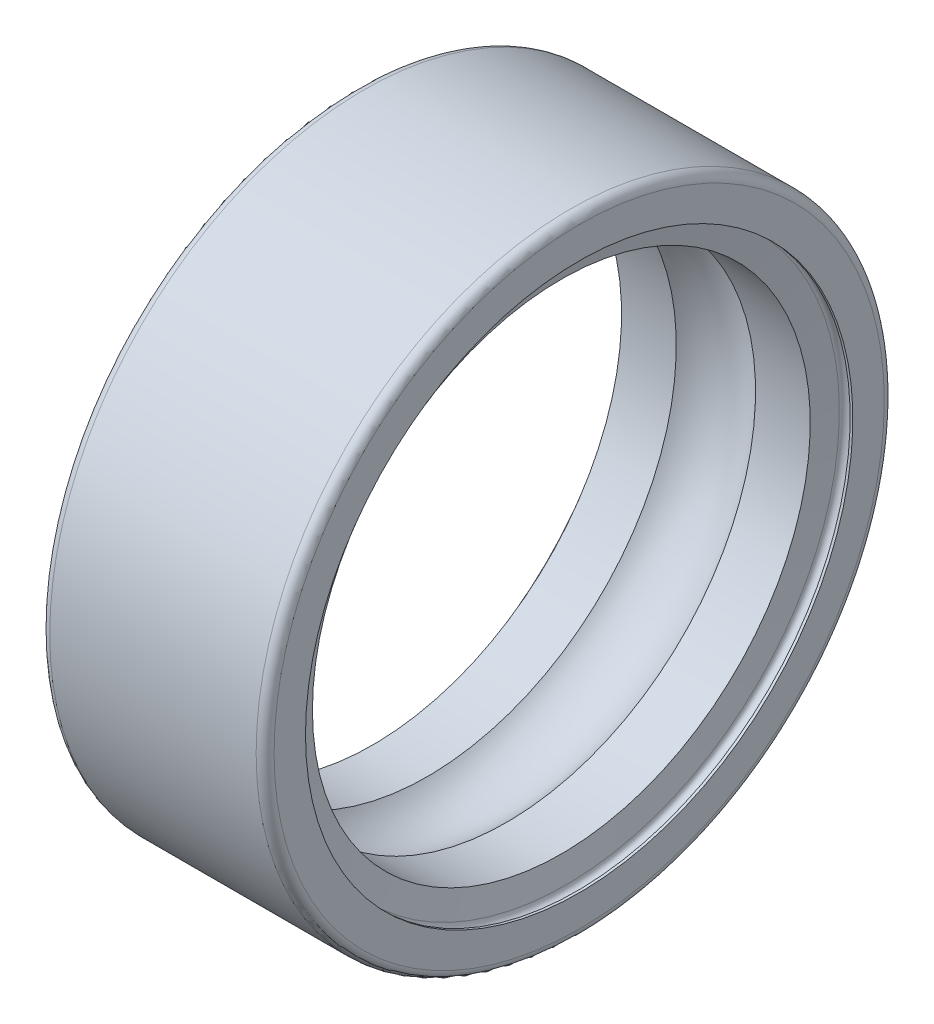
SolidWorks part; units mm, degrees
ref_plane "Front Plane" through (0, 0, 0) normal (0, 0, 1) x (1, 0, 0)
ref_plane "Top Plane" through (0, 0, 0) normal (0, 1, 0) x (1, 0, 0)
ref_plane "Right Plane" through (0, 0, 0) normal (1, 0, 0) x (0, 0, -1)
ref_plane "Plane1" through (0, 0, 0) normal (0, 0, 1) x (1, 0, 0)
sketch "Sketch1" plane through (0, 0, 0) normal (0, 0, 1) x (1, 0, 0)
  line L0 (0, 6.8) -> (0, 6.1)
  line L1 (0, 6.1) -> (0.06, 6.1)
  line L2 (0.3, 6.1) -> (0.3973, 5.548)
  line L3 (0.3973, 5.548) -> (1.6165, 5.548)
  line L4 (3.3835, 5.548) -> (4.6027, 5.548)
  line L5 (4.6027, 5.548) -> (4.7, 6.1)
  line L6 (4.94, 6.1) -> (5, 6.1)
  line L7 (5, 6.1) -> (5, 6.8)
  line L8 (4.8, 7) -> (0.2, 7)
  line L9 (50, 0) -> (-50, 0) construction
  arc A0 (0.06, 6.1) -> (0.3, 6.1) centre (0.18, 6.1) cw
  arc A1 (1.6165, 5.548) -> (3.3835, 5.548) centre (2.5, 4.75) cw
  arc A2 (4.7, 6.1) -> (4.94, 6.1) centre (4.82, 6.1) cw
  arc A3 (5, 6.8) -> (4.8, 7) centre (4.8, 6.8) ccw
  arc A4 (0.2, 7) -> (0, 6.8) centre (0.2, 6.8) ccw
revolve "Revolve1" add sketch "Sketch1" angle 360 about L9
